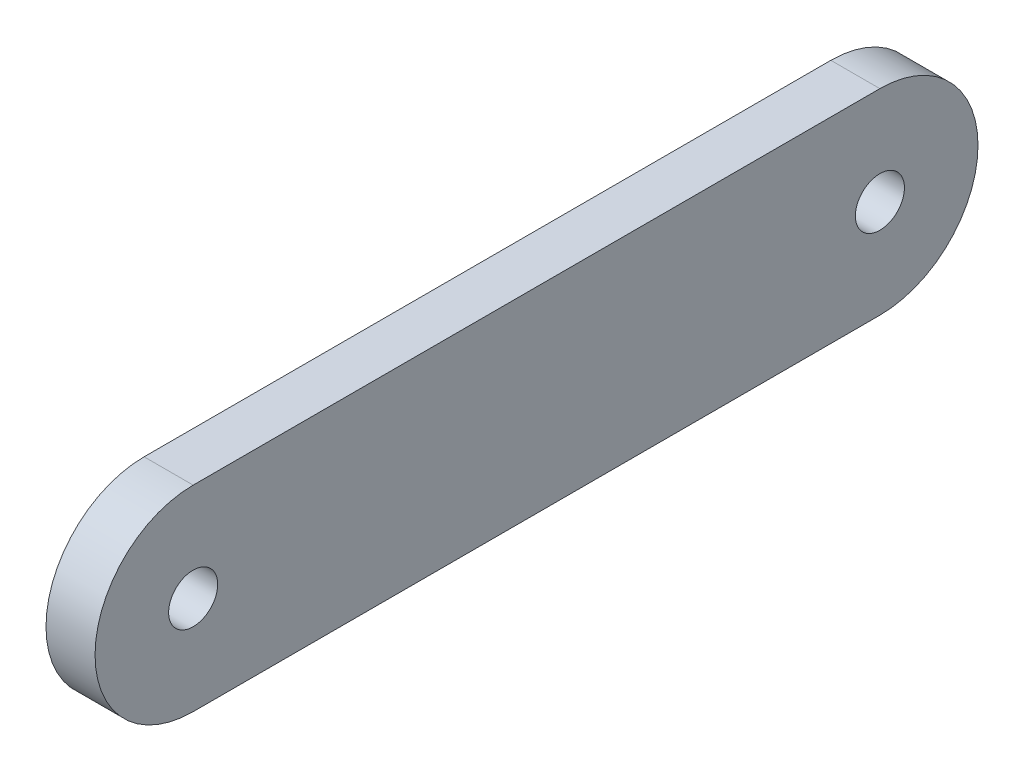
SolidWorks part; units mm, degrees
ref_plane "Front Plane" through (0, 0, 0) normal (0, 0, 1) x (1, 0, 0)
ref_plane "Top Plane" through (0, 0, 0) normal (0, 1, 0) x (1, 0, 0)
ref_plane "Right Plane" through (0, 0, 0) normal (1, 0, 0) x (0, 0, -1)
sketch "Sketch1" plane through (0, 0, 0) normal (1, 0, 0) x (0, 0, -1)
  line L0 (0, 0) -> (70, 0) construction
  line L1 (0, 10) -> (70, 10)
  line L2 (0, -10) -> (70, -10)
  arc A0 (0, 10) -> (0, -10) centre (0, 0) ccw
  arc A1 (70, -10) -> (70, 10) centre (70, 0) ccw
  circle A2 centre (0, 0) radius 2.5
  circle A3 centre (70, 0) radius 2.5
  point P3 (35, 0)
  dimension "D1" = 10
  dimension "D3" = 5
  dimension "D4" = 5
  dimension "D2" = 70
extrude "Boss-Extrude1" add sketch "Sketch1" along normal blind 5
